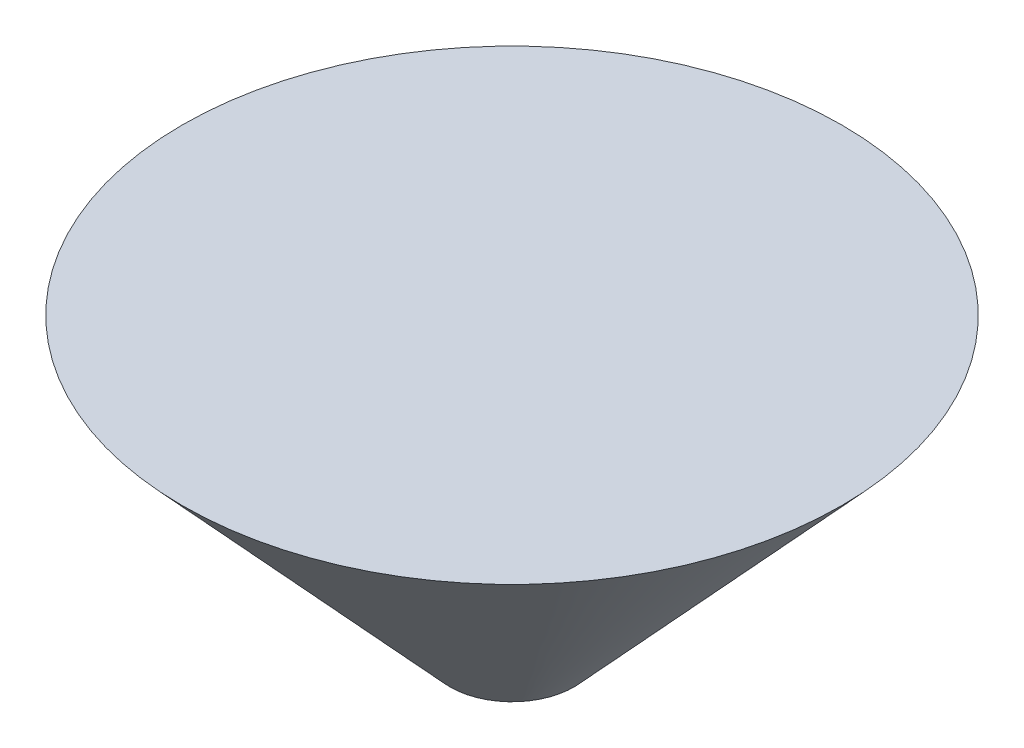
SolidWorks part; units mm, degrees
material "Nylon 101"
ref_plane "Alzado" through (0, 0, 0) normal (0, 0, 1) x (1, 0, 0)
ref_plane "Planta" through (0, 0, 0) normal (0, 1, 0) x (1, 0, 0)
ref_plane "Vista lateral" through (0, 0, 0) normal (1, 0, 0) x (0, 0, -1)
sketch "Sketch1" plane through (0, 0, 0) normal (0, 0, 1) x (1, 0, 0)
  line L0 (0, 0) -> (17, 0)
  line L1 (17, 0) -> (3.2, -15)
  line L2 (3.2, -15) -> (0, -15)
  line L3 (0, -15) -> (0, 0)
  line L4 (0, -19) -> (0, 4) construction
revolve "Cono_de_union" add sketch "Sketch1" angle 360 about L4
